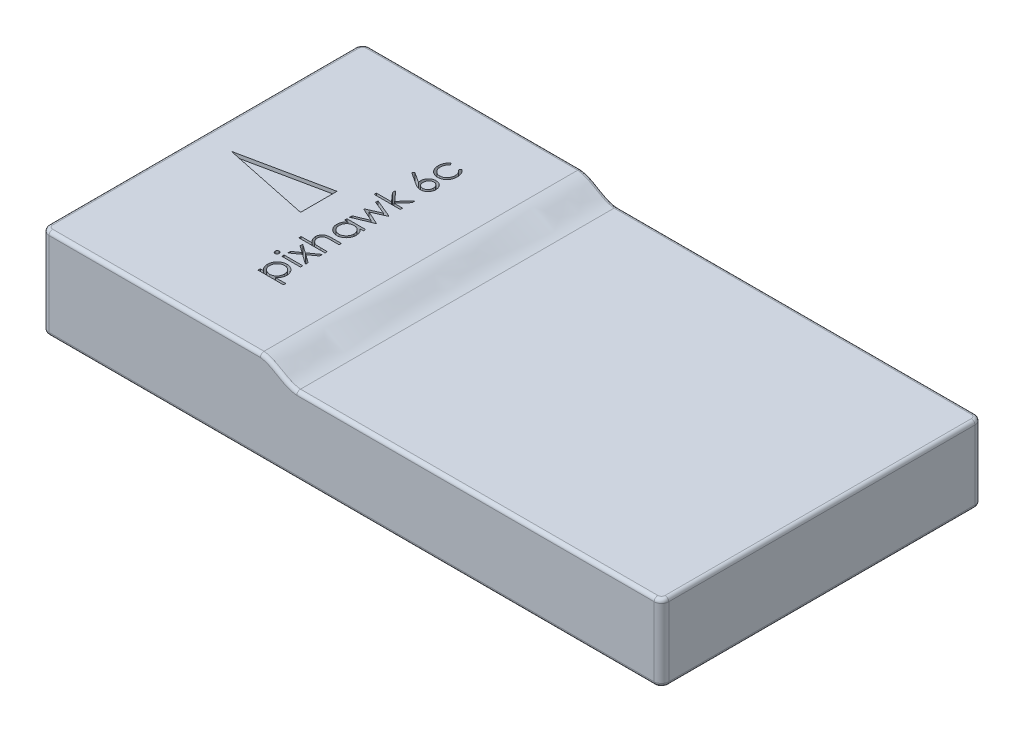
SolidWorks part; units mm, degrees
material "ABS"
ref_plane "Front Plane" through (0, 0, 0) normal (0, 0, 1) x (1, 0, 0)
ref_plane "Top Plane" through (0, 0, 0) normal (0, 1, 0) x (1, 0, 0)
ref_plane "Right Plane" through (0, 0, 0) normal (1, 0, 0) x (0, 0, -1)
sketch "Sketch1" plane through (0, 0, 0) normal (0, 1, 0) x (1, 0, 0)
  line L0 (-42.5, 22) -> (-42.5, -22)
  line L1 (-42.5, -22) -> (42.5, -22)
  line L2 (42.5, -22) -> (42.5, 22)
  line L3 (42.5, 22) -> (-42.5, 22)
  point P5 (0, -22)
  point P7 (42.5, 0)
  dimension "D1" = 44
  dimension "D2" = 85
sketch "Sketch2" plane through (0, 0, 0) normal (0, 0, 1) x (1, 0, 0)
  line L0 (42.5, 0) -> (-42.5, 0) construction
  line L1 (42.5, 0) -> (-42.5, 0) construction
  line L2 (-42.5, 12.5) -> (-12.5, 12.5)
  line L3 (42.5, 10.5) -> (-7.5, 10.5)
  line L4 (-42.5, 0) -> (-42.5, 12.5) construction
  line L5 (42.5, 0) -> (42.5, 10.5) construction
  line L6 (-42.5, 12.5) -> (-42.5, 22.5)
  line L7 (-42.5, 22.5) -> (42.5, 22.5)
  line L8 (42.5, 22.5) -> (42.5, 10.5)
  spline S0 degree 3 poles (-12.5, 12.5) (-10.6234, 12.323) (-9.3766, 10.677) (-7.5, 10.5) knots 0 0 0 0 1 1 1 1
  dimension "D1" = 12.5
  dimension "D2" = 10.5
  dimension "D3" = 30
  dimension "D4" = 50
  dimension "D5" = 1.6
  dimension "D6" = 1.6
  dimension "D7" = 0.5
  dimension "D8" = 0.5
  dimension "D9" = 10
extrude "Boss-Extrude1" add sketch "Sketch1" along normal blind 15
extrude "Cut-Extrude1" cut sketch "Sketch2" against normal through all both and the other way through all
sketch "Sketch3" plane through (0, 12.5, 0) normal (0, 1, 0) x (1, 0, 0)
  line L0 (-20, 22) -> (-20, -22) construction
  line L1 (-42.5, 22) -> (-12.5, 22) construction
  line L2 (-42.5, -22) -> (-12.5, -22) construction
  line L3 (-12.5, 22) -> (-12.5, -22) construction
  text T0 "pixhawk 6c      "
  point P6 (-20, 0)
  dimension "D1" = 20
  dimension "D2" = 12.5
  dimension "D3" = 22
extrude "Cut-Extrude2" cut sketch "Sketch3" against normal blind 2
fillet "Fillet1" radius 1 4 edges at (-42.5, 6.25, -22) (42.5, 5.25, -22) (42.5, 5.25, 22) (-42.5, 6.25, 22)
fillet "Fillet2" radius 0.5 12 edges at (-27, 12.5, -22) (-42.2071, 12.5, -21.7071) (-42.5, 12.5, 0) (-42.2071, 12.5, 21.7071) (17, 10.5, -22) (42.2071, 10.5, -21.7071) (42.5, 10.5, 0) (42.2071, 10.5, 21.7071) (-27, 12.5, 22) (17, 10.5, 22)
fillet "Fillet3" radius 0.5 8 edges at (-42.2071, 0, 21.7071) (-42.5, 0, 0) (-42.2071, 0, -21.7071) (0, 0, -22) (42.2071, 0, -21.7071) (42.5, 0, 0) (42.2071, 0, 21.7071) (0, 0, 22)
sketch "Sketch4" plane through (0, 12.5, 0) normal (0, 1, 0) x (1, 0, 0)
  line L0 (0, 0) -> (-42.5, 0) construction
  line L1 (-42.5, -21) -> (-42.5, 21) construction
  line L2 (-38.5, 0) -> (-26.5, 2.5)
  line L3 (-26.5, 2.5) -> (-26.5, -2.5)
  line L4 (-26.5, -2.5) -> (-38.5, 0)
  point P8 (-26.5, 0)
  dimension "D1" = 4
  dimension "D2" = 12
  dimension "D3" = 5
extrude "Cut-Extrude3" cut sketch "Sketch4" against normal blind 0.5
